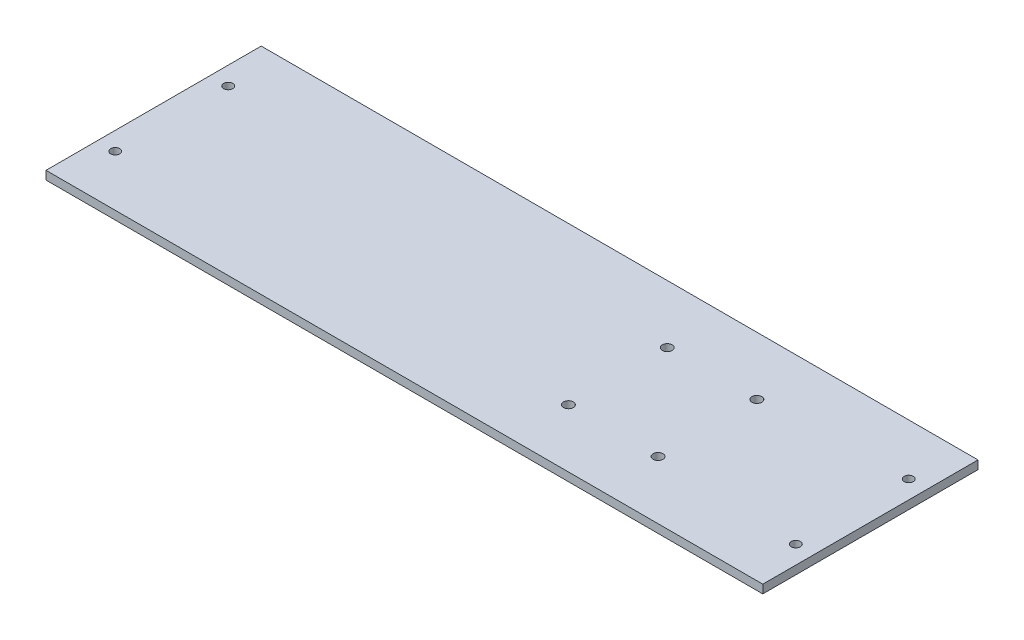
SolidWorks part; units mm, degrees
ref_plane "Front Plane" through (0, 0, 0) normal (0, 0, 1) x (1, 0, 0)
ref_plane "Top Plane" through (0, 0, 0) normal (0, 1, 0) x (1, 0, 0)
ref_plane "Right Plane" through (0, 0, 0) normal (1, 0, 0) x (0, 0, -1)
sketch "Sketch1" plane through (0, 0, 0) normal (0, 1, 0) x (1, 0, 0)
  line L1 (-253.8, 76.2) -> (253.8, 76.2)
  line L2 (-253.8, 76.2) -> (-253.8, -76.2)
  line L3 (-253.8, -76.2) -> (253.8, -76.2)
  line L4 (253.8, 76.2) -> (253.8, -76.2)
  line L5 (-253.8, 76.2) -> (253.8, -76.2) construction
  line L6 (-253.8, -76.2) -> (253.8, 76.2) construction
  point P0 (0, 0)
  dimension "D1" = 507.6
  dimension "D2" = 152.4
extrude "Boss-Extrude1" add sketch "Sketch1" along normal blind 6
sketch "Sketch2" plane through (0, 6, 0) normal (0, 1, 0) x (1, 0, 0)
  line L2 (240.96, 76.2) -> (240.96, 40) construction
  line L3 (253.8, 76.2) -> (-253.8, 76.2) construction
  line L4 (240.96, -40) -> (240.96, -76.2) construction
  line L5 (-253.8, -76.2) -> (253.8, -76.2) construction
  line L6 (240.96, 40) -> (253.8, 40) construction
  line L7 (253.8, -76.2) -> (253.8, 76.2) construction
  line L8 (240.96, -40) -> (253.8, -40) construction
  circle A0 centre (240.96, 40) radius 3.25
  circle A1 centre (240.96, -40) radius 3.25
  circle A2 centre (-240.96, -40) radius 3.25
  circle A3 centre (-240.96, 40) radius 3.25
  point P5 (0, 0)
  point P15 (0, 0)
  dimension "D1" = 6.5
  dimension "D2" = 80
  dimension "D3" = 12.84
  dimension "D4" = 2
extrude "Cut-Extrude1" cut sketch "Sketch2" against normal through all
sketch "Sketch3" plane through (0, 6, 0) normal (0, 1, 0) x (1, 0, 0)
  line L0 (159.93, 76.2) -> (159.93, -76.2) construction
  line L1 (253.8, 76.2) -> (-253.8, 76.2) construction
  line L2 (-253.8, -76.2) -> (253.8, -76.2) construction
  line L3 (253.8, -76.2) -> (253.8, 76.2) construction
  line L4 (61.43, 76.2) -> (61.43, -76.2) construction
  line L5 (159.93, 35) -> (138.43, 35) construction
  line L6 (138.43, 38.5) -> (138.43, 76.2) construction
  line L7 (74.93, -38.5) -> (74.93, -76.2) construction
  circle A0 centre (138.43, 35) radius 3.5
  circle A1 centre (74.93, 35) radius 3.5
  circle A2 centre (74.93, -35) radius 3.5
  circle A3 centre (138.43, -35) radius 3.5
  dimension "D4" = 7
  dimension "D1" = 93.87
  dimension "D2" = 98.5
  dimension "D3" = 21.5
  dimension "D5" = 2
  dimension "D6" = 2
extrude "Cut-Extrude2" cut sketch "Sketch3" against normal through all
